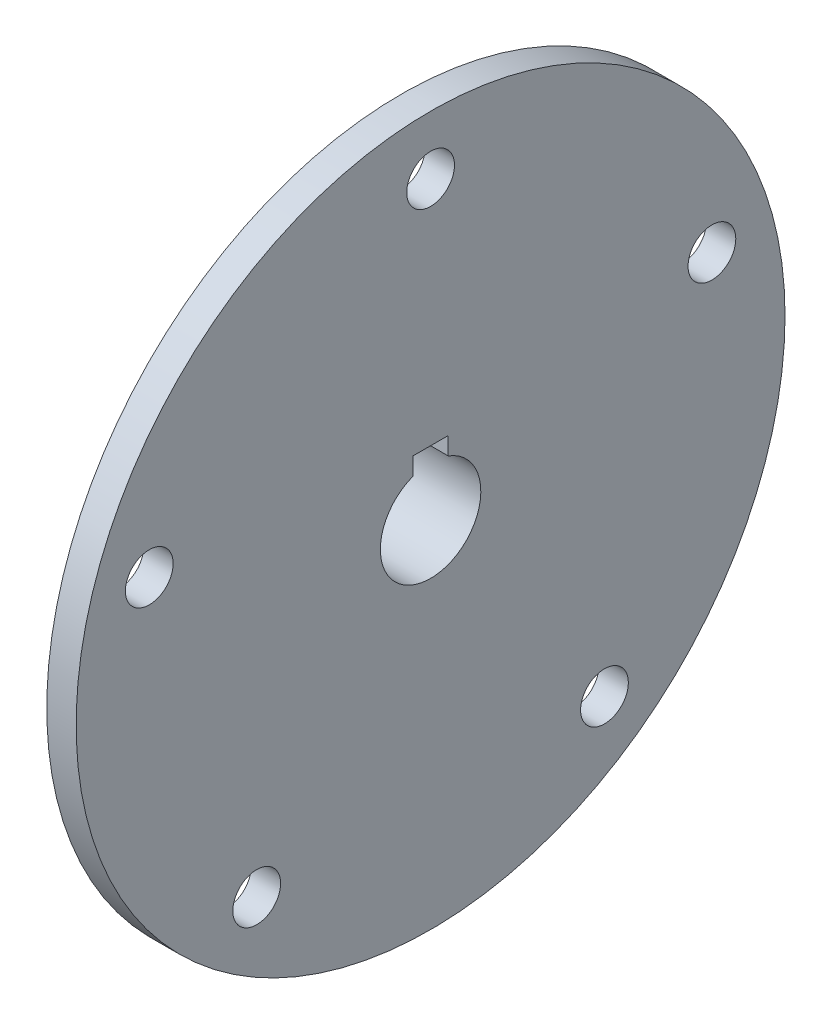
SolidWorks part; units mm, degrees
material "Alloy Steel"
ref_plane "Front Plane" through (0, 0, 0) normal (0, 0, 1) x (1, 0, 0)
ref_plane "Top Plane" through (0, 0, 0) normal (0, 1, 0) x (1, 0, 0)
ref_plane "Right Plane" through (0, 0, 0) normal (1, 0, 0) x (0, 0, -1)
sketch "Sketch1" plane through (0, 0, 0) normal (1, 0, 0) x (0, 0, -1)
  circle A0 centre (0, 0) radius 60.325
  dimension "D1" = 120.65
extrude "Boss-Extrude1" add sketch "Sketch1" against normal blind 5
sketch "Sketch2" plane through (0, 0, 0) normal (1, 0, 0) x (0, 0, -1)
  line L0 (0, 60.325) -> (0, -60.325) construction
  circle A1 centre (0, 0) radius 60.325 construction
  circle A16 centre (0, 50.343) radius 4.064
  circle A17 centre (47.879, 15.5568) radius 4.064
  circle A18 centre (29.5908, -40.7283) radius 4.064
  circle A19 centre (-29.5908, -40.7283) radius 4.064
  circle A20 centre (-47.879, 15.5568) radius 4.064
extrude "Cut-Extrude1" cut sketch "Sketch2" against normal through all
sketch "Sketch11" plane through (-5, 0, 0) normal (-1, 0, 0) x (0, 0, 1)
  circle A0 centre (0, 0) radius 17.5
  dimension "D1" = 35
extrude "Boss-Extrude3" add sketch "Sketch11" along normal blind 30
sketch "Sketch12" plane through (-35, 0, 0) normal (-1, 0, 0) x (0, 0, 1)
  line L0 (0, 5.55) -> (0, 8.55) construction
  line L1 (0, 8.55) -> (0, 11.0064) construction
  line L2 (0, 11.0064) -> (-3, 11.0064)
  line L3 (-3, 11.0064) -> (-3, 8.0064)
  line L4 (0, 11.0064) -> (3, 11.0064)
  line L5 (3, 11.0064) -> (3, 8.0064)
  line L6 (-3, 8.0064) -> (3, 8.0064) construction
  arc A0 (-3, 8.0064) -> (3, 8.0064) centre (0, 0) ccw
  dimension "D1" = 17.1
  dimension "D2" = 3
  dimension "D3" = 3
extrude "Cut-Extrude5" cut sketch "Sketch12" against normal through all
